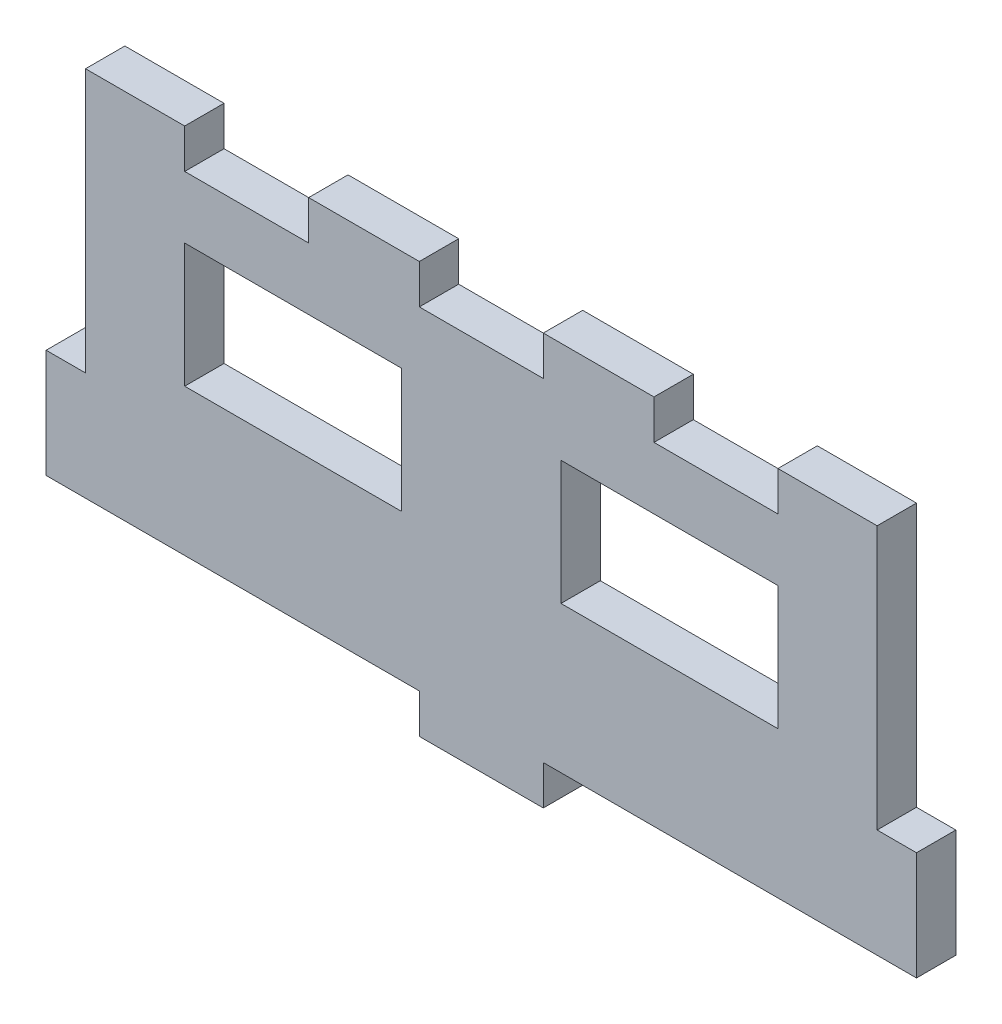
SolidWorks part; units mm, degrees
ref_plane "Front Plane" through (0, 0, 0) normal (0, 0, 1) x (1, 0, 0)
ref_plane "Top Plane" through (0, 0, 0) normal (0, 1, 0) x (1, 0, 0)
ref_plane "Right Plane" through (0, 0, 0) normal (1, 0, 0) x (0, 0, -1)
sketch "Sketch3" plane through (0, 0, 0) normal (0, 0, 1) x (1, 0, 0)
  line L0 (0, 0) -> (0, -60) construction
  line L1 (-127.7, 60) -> (127.7, 60)
  line L2 (-127.7, 60) -> (-127.7, -60)
  line L3 (-127.7, -60) -> (127.7, -60)
  line L4 (127.7, 60) -> (127.7, -60)
  line L5 (0, 0) -> (127.7, 0) construction
  line L6 (127.7, -25) -> (140.4, -25)
  line L7 (-20, -60) -> (20, -60)
  line L8 (-20, -60) -> (-20, -72.7)
  line L9 (-20, -72.7) -> (20, -72.7)
  line L10 (20, -60) -> (20, -72.7)
  line L11 (-127.7, -60) -> (-140.4, -60)
  line L12 (-127.7, -60) -> (-127.7, -25)
  line L13 (-127.7, -25) -> (-140.4, -25)
  line L14 (-140.4, -60) -> (-140.4, -25)
  line L15 (140.4, -60) -> (140.4, -25)
  line L16 (127.7, -60) -> (140.4, -60)
  line L17 (127.7, -60) -> (127.7, -25)
  dimension "D1" = 255.4
  dimension "D2" = 120
  dimension "D3" = 40
  dimension "D4" = 12.7
  dimension "D5" = 107.7
  dimension "D6" = 35
  dimension "D7" = 12.7
extrude "Boss-Extrude1" add sketch "Sketch3" along normal blind 12.7 contours L1 L4 L3 L2 | L9 L10 L7 L8 | L12 L11 L14 L13 | L17 L6 L15 L16
sketch "Sketch4" plane through (0, 0, 12.7) normal (0, 0, 1) x (1, 0, 0)
  line L0 (-127.7, 60) -> (127.7, 60) construction
  line L1 (-20, 60) -> (20, 60)
  line L2 (-20, 60) -> (-20, 47.3)
  line L3 (-20, 47.3) -> (20, 47.3)
  line L4 (20, 60) -> (20, 47.3)
  line L5 (20, -60) -> (20, -72.7) construction
  line L6 (-20, -60) -> (-20, -72.7) construction
  dimension "D1" = 12.7
extrude "Cut-Extrude1" cut sketch "Sketch4" against normal blind 12.7
sketch "Sketch5" plane through (0, 0, 12.7) normal (0, 0, 1) x (1, 0, 0)
  line L0 (-127.7, 60) -> (-20, 60) construction
  line L1 (-95.7, 60) -> (-55.7, 60)
  line L2 (-95.7, 60) -> (-95.7, 47.3)
  line L3 (-95.7, 47.3) -> (-55.7, 47.3)
  line L4 (-55.7, 60) -> (-55.7, 47.3)
  line L5 (-127.7, 60) -> (-127.7, -25) construction
  line L7 (20, 60) -> (127.7, 60) construction
  line L8 (55.7, 60) -> (95.7, 60)
  line L9 (55.7, 60) -> (55.7, 47.3)
  line L10 (55.7, 47.3) -> (95.7, 47.3)
  line L11 (95.7, 60) -> (95.7, 47.3)
  line L12 (127.7, 60) -> (127.7, -25) construction
  line L13 (-95.7, 27.3) -> (-25.7, 27.3)
  line L14 (-95.7, 27.3) -> (-95.7, -12.7)
  line L15 (-95.7, -12.7) -> (-25.7, -12.7)
  line L16 (-25.7, 27.3) -> (-25.7, -12.7)
  line L17 (25.7, 27.3) -> (95.7, 27.3)
  line L18 (25.7, 27.3) -> (25.7, -12.7)
  line L19 (25.7, -12.7) -> (95.7, -12.7)
  line L20 (95.7, 27.3) -> (95.7, -12.7)
  dimension "D1" = 12.7
  dimension "D2" = 40
  dimension "D3" = 32
  dimension "D4" = 12.7
  dimension "D5" = 40
  dimension "D6" = 32
  dimension "D7" = 40
  dimension "D8" = 20
  dimension "D9" = 70
extrude "Cut-Extrude2" cut sketch "Sketch5" against normal blind 12.7
